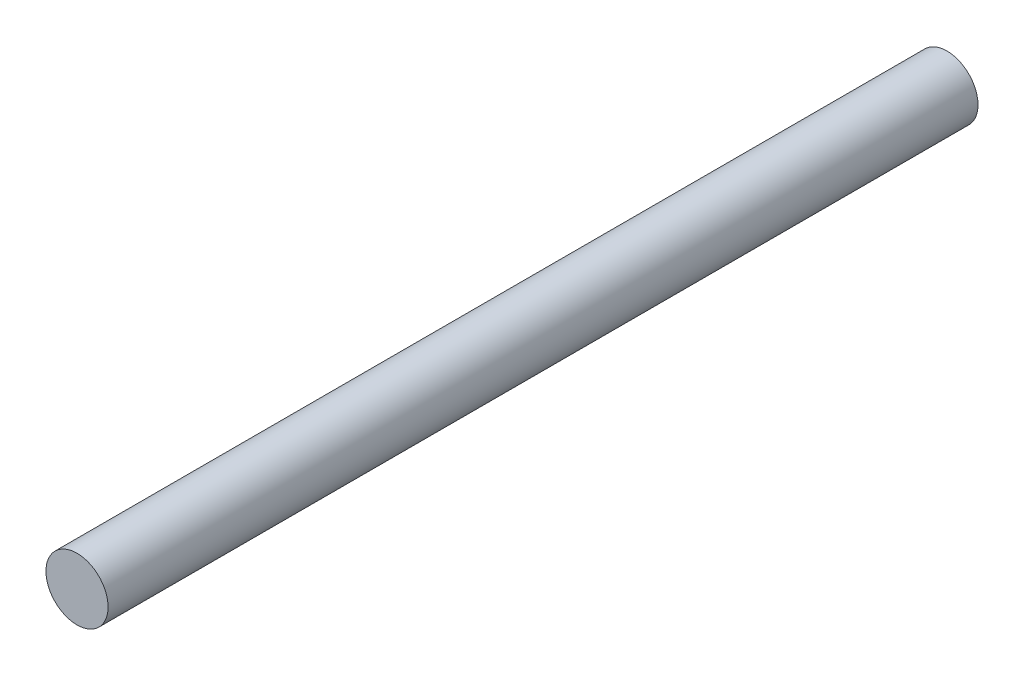
SolidWorks part; units mm, degrees
material "Plain Carbon Steel"
ref_plane "Front Plane" through (0, 0, 0) normal (0, 0, 1) x (1, 0, 0)
ref_plane "Top Plane" through (0, 0, 0) normal (0, 1, 0) x (1, 0, 0)
ref_plane "Right Plane" through (0, 0, 0) normal (1, 0, 0) x (0, 0, -1)
sketch "Sketch1" plane through (0, 0, 0) normal (0, 0, 1) x (1, 0, 0)
  circle A0 centre (0, 0) radius 1.5875
  dimension "D1" = 3.175
extrude "Body" add sketch "Sketch1" against normal blind 44.45
sketch "Sketch2" plane through (0, 0, 0) normal (0, 1, 0) x (1, 0, 0)
  line L0 (0, 22.225) -> (-8.5875, 22.225) construction
  line L1 (-2.2429, 19.685) -> (-2.2429, 20.955)
  line L2 (-2.2429, 20.955) -> (-1.3335, 20.43)
  line L3 (-2.2429, 23.495) -> (-1.3335, 24.02)
  line L4 (-1.3335, 20.21) -> (-2.2429, 19.685)
  line L5 (-1.3335, 24.24) -> (-2.2429, 24.765)
  line L6 (-2.2429, 24.765) -> (-2.2429, 23.495)
  line L9 (0, 0) -> (0, 44.45) construction
  line L10 (1.5875, 44.45) -> (-1.5875, 44.45) construction
  line L11 (1.5875, 44.45) -> (-1.5875, 44.45) construction
  arc A0 (-1.3335, 20.21) -> (-1.3335, 20.43) centre (-1.397, 20.32) ccw
  arc A1 (-1.3335, 24.24) -> (-1.3335, 24.02) centre (-1.397, 24.13) cw
  point P15 (0, 22.225)
  dimension "D4" = 0.254
  dimension "D3" = 1.27
  dimension "D1" = 60
  dimension "D2" = 60
  dimension "D5" = 1.397
  dimension "D6" = 1.905
revolve "WireSlots" [suppressed] cut sketch "Sketch2" angle 360 about L9
